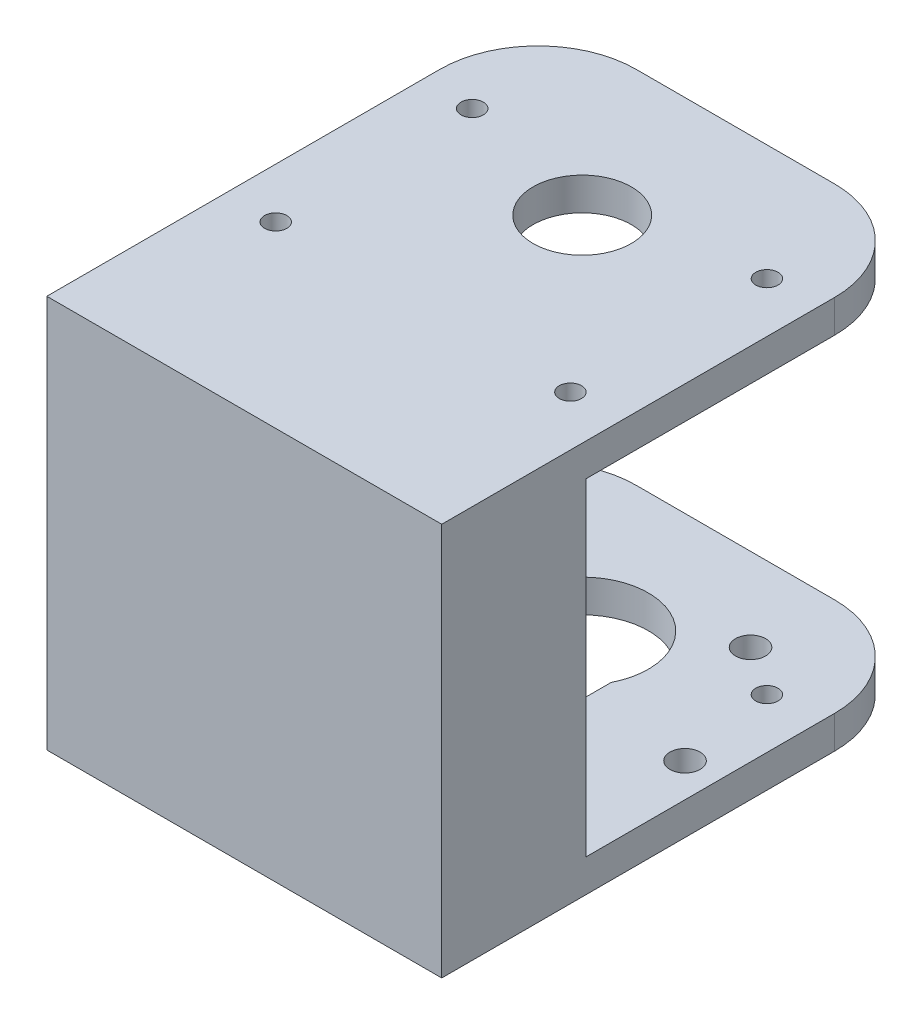
SolidWorks part; units mm, degrees
ref_plane "Front Plane" through (0, 0, 0) normal (0, 0, 1) x (1, 0, 0)
ref_plane "Top Plane" through (0, 0, 0) normal (0, 1, 0) x (1, 0, 0)
ref_plane "Right Plane" through (0, 0, 0) normal (1, 0, 0) x (0, 0, -1)
sketch "Sketch2" plane through (0, 0, 0) normal (0, 1, 0) x (1, 0, 0)
  line L0 (0, 32.7) -> (0, -32.7) construction
  line L1 (15.15, -32.7) -> (-15.15, -32.7)
  line L2 (30.15, -17.7) -> (30.15, 17.7)
  line L3 (15.15, 32.7) -> (-15.15, 32.7)
  line L4 (-30.15, -17.7) -> (-30.15, 17.7)
  line L5 (30.15, -32.7) -> (-30.15, 32.7) construction
  line L6 (30.15, 32.7) -> (-30.15, -32.7) construction
  line L7 (30.15, 0) -> (-30.15, 0) construction
  line L8 (-15, 20) -> (-15, -20) construction
  line L9 (-22.5, 15) -> (-22.5, -15) construction
  line L10 (-15, 20) -> (15, 20) construction
  line L12 (-9, 4.7163) -> (-9, -16.9)
  line L13 (-9, -16.9) -> (9, -16.9)
  line L14 (9, 4.7163) -> (9, -16.9)
  line L15 (-9, 4.7163) -> (9, -16.9) construction
  line L16 (-9, -16.9) -> (9, 4.7163) construction
  line L17 (0, 19.4) -> (0, -16.9) construction
  arc A0 (15.15, -32.7) -> (30.15, -17.7) centre (15.15, -17.7) ccw
  arc A1 (-15.15, -32.7) -> (-30.15, -17.7) centre (-15.15, -17.7) cw
  arc A2 (-15.15, 32.7) -> (-30.15, 17.7) centre (-15.15, 17.7) ccw
  arc A3 (30.15, 17.7) -> (15.15, 32.7) centre (15.15, 17.7) ccw
  circle A4 centre (-15, 20) radius 2.3
  circle A5 centre (-25, 0) radius 2.3
  circle A6 centre (-15, -20) radius 2.3
  circle A7 centre (-22.5, -15) radius 1.7
  circle A8 centre (-22.5, 15) radius 1.7
  circle A9 centre (15, 20) radius 2.3
  circle A10 centre (22.5, 15) radius 1.7
  circle A11 centre (25, 0) radius 2.3
  circle A12 centre (22.5, -15) radius 1.7
  circle A13 centre (15, -20) radius 2.3
  arc A14 (9, 4.7163) -> (-9, 4.7163) centre (0, 9.3) ccw
  point P0 (0, 0)
  point P28 (73.6135, -0.9222)
  point P33 (0, -6.0918)
  point P36 (-15, 0)
  point P37 (-22.5, 0)
  point P38 (9.2048, 5.1428)
  point P53 (118.696, 44.65)
  point P54 (0, 0)
  point P55 (73.1247, -3.8)
  point P58 (5.7081, 2.6734)
  point P59 (-6.7085, 4.0078)
  point P60 (-9, 4.356)
  dimension "D3" = 15
  dimension "D4" = 4.6
  dimension "D5" = 4.6
  dimension "D6" = 4.6
  dimension "D7" = 3.4
  dimension "D8" = 3.4
  dimension "D14" = 20.2
  dimension "D1" = 60.3
  dimension "D2" = 65.4
  dimension "D9" = 15
  dimension "D10" = 22.5
  dimension "D11" = 25
  dimension "D12" = 20
  dimension "D13" = 15
  dimension "D15" = 36.3
  dimension "D16" = 18
  dimension "D17" = 0.6
extrude "Boss-Extrude1" add sketch "Sketch2" along normal blind 5
sketch "Sketch3" plane through (0, 0, 0) normal (0, -1, 0) x (1, 0, 0)
  line L0 (-30.15, 17.7) -> (-30.15, 42.3)
  line L1 (-30.15, 42.3) -> (30.15, 42.3)
  line L2 (30.15, 42.3) -> (30.15, 17.7)
  line L3 (30.15, 17.7) -> (30.15, -17.7) construction
  line L4 (30.15, 17.7) -> (15.15, 32.7)
  line L5 (15.15, 32.7) -> (-15.15, 32.7)
  line L6 (-15.15, 32.7) -> (-30.15, 17.7)
  line L7 (15.15, -32.7) -> (-15.15, -32.7) construction
  point P14 (30.15, 42.3)
  dimension "D1" = 75
extrude "Boss-Extrude2" add sketch "Sketch3" against normal blind 5
sketch "Sketch4" plane through (0, 5, 0) normal (0, 1, 0) x (1, 0, 0)
  line L0 (30.15, -42.3) -> (30.15, 17.7) construction
  line L1 (-30.15, -42.3) -> (30.15, -42.3)
  line L2 (-30.15, -42.3) -> (-30.15, -27.3)
  line L3 (-30.15, -27.3) -> (30.15, -27.3)
  line L4 (30.15, -42.3) -> (30.15, -27.3)
  dimension "D1" = 15
extrude "Boss-Extrude3" add sketch "Sketch4" along normal blind 50
sketch "Sketch5" plane through (0, 55, 0) normal (0, 1, 0) x (1, 0, 0)
  line L0 (15.15, 32.7) -> (-15.15, 32.7) construction
  line L1 (-30.15, -42.3) -> (30.15, -42.3)
  line L2 (-30.15, -42.3) -> (-30.15, 17.7)
  line L3 (-15.15, 32.7) -> (15.15, 32.7)
  line L4 (30.15, -42.3) -> (30.15, 17.7)
  line L5 (30.15, -27.3) -> (30.15, 17.7) construction
  arc A0 (-30.15, 17.7) -> (-15.15, 32.7) centre (-15.15, 17.7) cw
  arc A1 (15.15, 32.7) -> (30.15, 17.7) centre (15.15, 17.7) cw
  circle A2 centre (-22.5, 15) radius 1.7
  circle A3 centre (-22.5, -15) radius 1.7
  circle A4 centre (22.5, 15) radius 1.7
  circle A5 centre (22.5, -15) radius 1.7
  circle A6 centre (0, 9.3) radius 7.5
  dimension "D1" = 15
  dimension "D2" = 3.4
  dimension "D3" = 3.4
  dimension "D4" = 3.4
  dimension "D5" = 3.4
  dimension "D6" = 15
extrude "Boss-Extrude4" add sketch "Sketch5" along normal blind 5
sketch "Sketch7" plane through (0, 0, 27.3) normal (0, 0, -1) x (-1, 0, 0)
  line L0 (30.15, 55) -> (30.15, 5) construction
  line L1 (-30.15, 55) -> (30.15, 55)
  line L2 (-30.15, 55) -> (-30.15, 5)
  line L3 (-30.15, 5) -> (30.15, 5)
  line L4 (30.15, 55) -> (30.15, 5)
  line L5 (-30.15, 5) -> (30.15, 5) construction
extrude "Boss-Extrude6" add sketch "Sketch7" along normal blind 7
